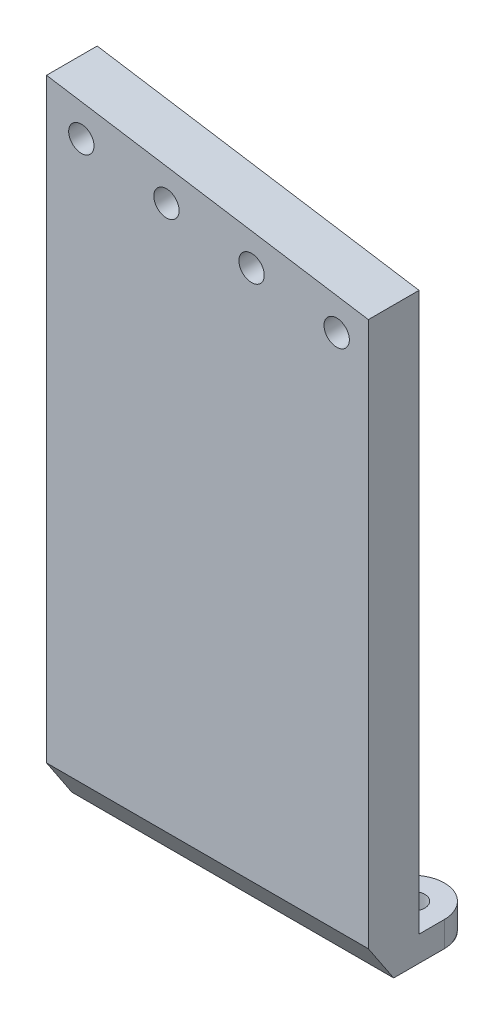
SolidWorks part; units mm, degrees
ref_plane "Front Plane" through (0, 0, 0) normal (0, 0, 1) x (1, 0, 0)
ref_plane "Top Plane" through (0, 0, 0) normal (0, 1, 0) x (1, 0, 0)
ref_plane "Right Plane" through (0, 0, 0) normal (1, 0, 0) x (0, 0, -1)
sketch "Sketch1" plane through (0, 0, 0) normal (0, 1, 0) x (1, 0, 0)
  line L1 (0, 0) -> (32.258, 0)
  line L2 (0, 0) -> (0, 7.62)
  line L3 (6.35, 7.62) -> (25.908, 7.62)
  line L4 (32.258, 0) -> (32.258, 7.62)
  arc A0 (0, 7.62) -> (6.35, 7.62) centre (3.175, 7.62) cw
  arc A1 (32.258, 7.62) -> (25.908, 7.62) centre (29.083, 7.62) ccw
  circle A2 centre (3.175, 7.62) radius 1.2065
  circle A3 centre (29.083, 7.62) radius 1.2065
  dimension "D7" = 2.413
  dimension "D8" = 2.413
  dimension "D1" = 6.35
  dimension "D2" = 6.35
  dimension "D3" = 32.258
  dimension "D4" = 7.62
  dimension "D5" = 7.62
  dimension "D6" = 7.62
extrude "Boss-Extrude1" add sketch "Sketch1" along normal blind 2.54
sketch "Sketch2" plane through (0, 2.54, 0) normal (0, 1, 0) x (1, 0, 0)
  line L0 (32.258, 0) -> (32.258, 7.62) construction
  line L1 (0, 0) -> (32.258, 0)
  line L2 (0, 0) -> (0, 5.08)
  line L3 (0, 5.08) -> (32.258, 5.08)
  line L4 (32.258, 0) -> (32.258, 5.08)
  dimension "D1" = 5.08
extrude "Boss-Extrude2" add sketch "Sketch2" along normal blind 60.96
sketch "Sketch4" plane through (0, 0, 0) normal (0, 0, 1) x (1, 0, 0)
  line L0 (32.258, 63.5) -> (0, 58.42)
  line L1 (0, 63.5) -> (0, 0) construction
  line L2 (0, 58.42) -> (0, 63.5)
  line L3 (0, 63.5) -> (32.258, 63.5)
  dimension "D1" = 5.08
extrude "Cut-Extrude2" cut sketch "Sketch4" against normal up to surface (5.08 mm away) up to face at (20.1613, 48.26, -5.08)
sketch "Sketch3" plane through (0, 0, -5.08) normal (0, 0, -1) x (-1, 0, 0)
  line L2 (0, 58.42) -> (0, 2.54) construction
  line L3 (-32.258, 63.5) -> (0, 58.42) construction
  line L4 (-3.175, 55.7059) -> (-28.7676, 59.7362)
  circle A0 centre (-28.7676, 59.7362) radius 1.27
  circle A1 centre (-20.2367, 58.3928) radius 1.27
  circle A2 centre (-11.7059, 57.0493) radius 1.27
  circle A3 centre (-3.175, 55.7059) radius 1.27
  dimension "D1" = 2.54
  dimension "D2" = 3.175
  dimension "D3" = 25.908
  dimension "D4" = 3.175
  dimension "D5" = 8.636
  dimension "D6" = 8.636
  dimension "D7" = 3.175
  dimension "D8" = 3.175
  dimension "D9" = 3.175
extrude "Cut-Extrude1" cut sketch "Sketch3" against normal up to surface (5.08 mm away) up to face at (16.129, 30.48, 0)
sketch "Sketch5" plane through (0, 0, 0) normal (-1, 0, 0) x (0, 0, 1)
  line L0 (0, 0) -> (-2.54, 0)
  line L1 (-7.62, 0) -> (0, 0) construction
  line L2 (-2.54, 0) -> (0, 3.81)
  line L3 (0, 58.42) -> (0, 0) construction
  line L4 (0, 3.81) -> (0, 0)
  dimension "D1" = 3.81
  dimension "D2" = 2.54
extrude "Cut-Extrude3" cut sketch "Sketch5" against normal up to surface (32.258 mm away) up to face at (32.258, 27.0933, -4.0217)
ref_plane "Plane1" through (0.627, -3.9813, 0) normal (-0.1556, 0.9878, 0) x (0.9878, 0.1556, 0)
sketch "Sketch6" plane through (0.627, -3.9813, 0) normal (-0.1556, 0.9878, 0) x (0.9878, 0.1556, 0)
  circle A0 centre (28.8119, 7.6479) radius 3.2194
extrude "Cut-Extrude4" cut sketch "Sketch6" against normal blind 2.54
ref_plane "Plane2" through (0, 0, 0) normal (-0.1556, 0.9878, 0) x (0.9878, 0.1556, 0)
sketch "Sketch7" plane through (0, 0, 0) normal (-0.1556, 0.9878, 0) x (0.9878, 0.1556, 0)
  circle A0 centre (3.216, 7.6159) radius 3.216
extrude "Cut-Extrude5" cut sketch "Sketch7" against normal blind 2.54
mirror "Mirror1" about plane through (32.258, 2.54, 0) normal (-1, 0, 0) of bodies 107
sketch "Sketch8" plane through (0, 0, -5.08) normal (0, 0, -1) x (-1, 0, 0)
  line L1 (-32.258, 63.5) -> (2.3799, 63.5)
  line L2 (-32.258, 63.5) -> (-32.258, -5.4947)
  line L3 (-32.258, -5.4947) -> (2.3799, -5.4947)
  line L4 (2.3799, 63.5) -> (2.3799, -5.4947)
extrude "Cut-Extrude7" cut sketch "Sketch8" against normal through all and the other way through all
